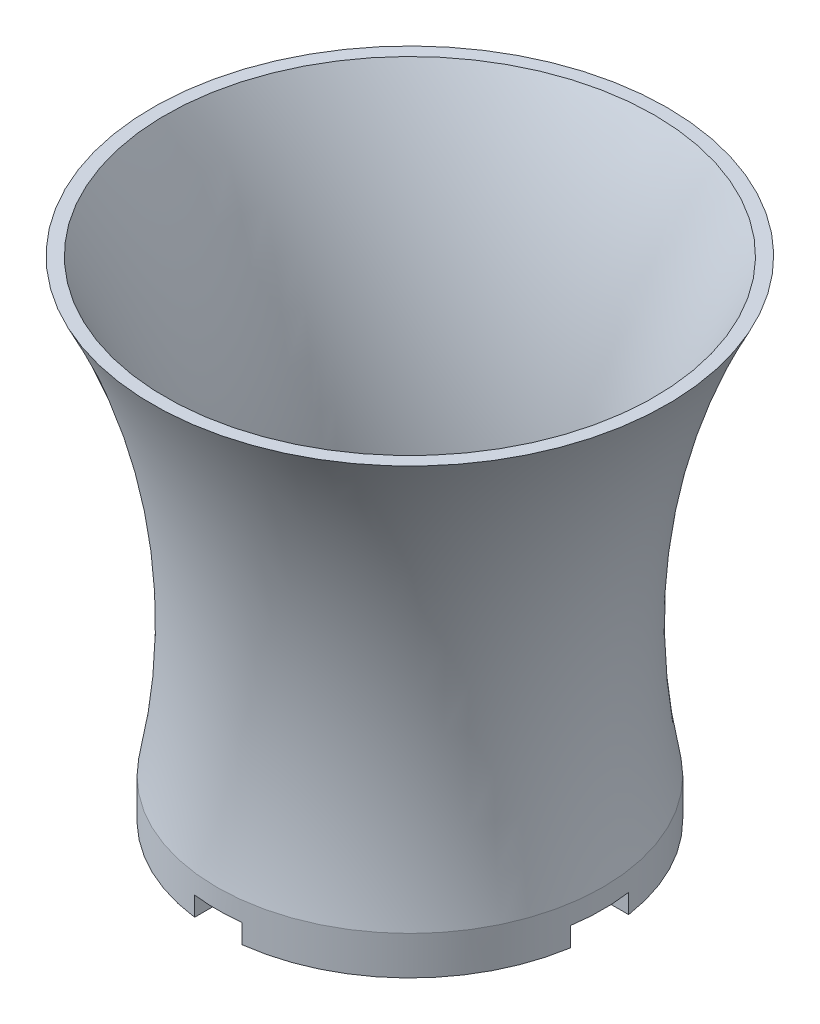
SolidWorks part; units mm, degrees
ref_plane "Front Plane" through (0, 0, 0) normal (0, 0, 1) x (1, 0, 0)
ref_plane "Top Plane" through (0, 0, 0) normal (0, 1, 0) x (1, 0, 0)
ref_plane "Right Plane" through (0, 0, 0) normal (1, 0, 0) x (0, 0, -1)
sketch "Sketch2" plane through (0, 0, 0) normal (0, 0, 1) x (1, 0, 0)
  line L0 (0, 0) -> (-35.56, 0)
  line L2 (-48.26, 88.9) -> (-50.8, 88.9)
  line L3 (-50.8, 88.9) -> (-48.26, 88.9) construction
  line L4 (0, 0) -> (0, 88.9) construction
  line L5 (-35.5254, 26.3207) -> (-32.9854, 26.3207) construction
  line L6 (-38.1, 0) -> (-38.1, -7.62)
  line L7 (-38.1, -7.62) -> (0, -7.62)
  line L8 (0, -7.62) -> (0, 0)
  arc A0 (-50.8, 88.9) -> (-38.1, 0) centre (-171.3551, 26.3207) cw
  arc A1 (-48.26, 88.9) -> (-35.56, 0) centre (-170.4492, 26.0873) cw
revolve "Revolve1" add sketch "Sketch2" angle 360 about L4
hole_wizard "9/64 (0.14063) Diameter Hole2" positions "Sketch8" profile "Sketch7" hole size "9/64" standard "ANSI Inch" end condition up to next
sketch "Sketch8" plane through (0, 0, 0) normal (0, 1, 0) x (1, 0, 0)
  point P0 (0, -28.7264)
  point P2 (-28.3897, 0)
  point P4 (0, 28.7264)
  point P6 (28.1202, 0)
  point P8 (17.8151, -20.1051)
  point P10 (17.8151, 19.4316)
  point P12 (-18.4213, 19.4316)
  point P14 (-18.4213, -20.1051)
  point P16 (0, 0)
sketch "Sketch7" plane through (0, 0, 28.7264) normal (1, 0, 0) x (0, 0, 1)
  line L0 (0, 0) -> (0, 7.62)
  line L1 (0, 7.62) -> (1.786, 7.62)
  line L2 (1.786, 7.62) -> (1.786, 0.5328)
  line L3 (1.786, 0.5328) -> (2.421, 0)
  line L5 (2.421, 0) -> (0, 0)
  line L6 (-1.786, 0.5328) -> (-2.421, 0) construction
  line L11 (0, -6.35) -> (0, 107.95) construction
  dimension "Thru Hole Dia." = 3.572
  dimension "Thru Hole Depth" = 7.62
  dimension "Near C'Sink Dia." = 4.842
  dimension "Near C'Sink Angle" = 100
hole_wizard "9/64 (0.14063) Diameter Hole3" positions "Sketch9" profile "Sketch10" hole size "9/64" standard "ANSI Inch" end condition up to next
sketch "Sketch9" plane through (0, -7.62, 0) normal (0, -1, 0) x (-1, 0, 0)
  point P0 (-6.3649, 18.9601)
  point P2 (7.51, 18.9601)
  point P4 (19.8357, 7.9141)
  point P6 (-19.2969, 7.9141)
  point P8 (-19.2969, -8.3856)
  point P10 (-7.0385, -21.3175)
  point P12 (7.9141, -21.3175)
  point P14 (19.8357, -8.857)
sketch "Sketch10" plane through (6.3649, -7.62, -18.9601) normal (1, 0, 0) x (0, 0, -1)
  line L0 (0, 0) -> (0, 7.62)
  line L1 (0, 7.62) -> (1.786, 7.62)
  line L2 (1.786, 7.62) -> (1.786, 0.5328)
  line L3 (1.786, 0.5328) -> (2.421, 0)
  line L5 (2.421, 0) -> (0, 0)
  line L6 (-1.786, 0.5328) -> (-2.421, 0) construction
  line L11 (0, -6.35) -> (0, 107.95) construction
  dimension "Thru Hole Dia." = 3.572
  dimension "Thru Hole Depth" = 7.62
  dimension "Near C'Sink Dia." = 4.842
  dimension "Near C'Sink Angle" = 100
sketch "Sketch11" plane through (0, -7.62, 0) normal (0, -1, 0) x (1, 0, 0)
  line L0 (-4.6966, 37.8094) -> (-4.6966, 30.7269)
  line L2 (4.6966, -37.8094) -> (4.6966, -30.7269)
  line L3 (-4.6966, -30.7269) -> (-4.6966, -37.8094)
  line L4 (37.6302, 5.9646) -> (30.5062, 5.9646)
  line L5 (37.7019, -5.4931) -> (30.5946, -5.4931)
  line L6 (4.6966, 30.7269) -> (4.6966, 37.8094)
  line L7 (-30.5062, 5.9646) -> (-37.6302, 5.9646)
  line L8 (-30.5946, -5.4931) -> (-37.7019, -5.4931)
  circle A0 centre (0, 0) radius 38.1 construction
  circle A1 centre (0, 0) radius 38.1 construction
  arc A5 (-37.6302, 5.9646) -> (-37.7019, -5.4931) centre (0, 0) ccw
  arc A6 (-4.6966, 30.7269) -> (-30.5062, 5.9646) centre (0, 0) ccw
  arc A7 (-30.5946, -5.4931) -> (-4.6966, -30.7269) centre (0, 0) ccw
  arc A8 (30.5062, 5.9646) -> (4.6966, 30.7269) centre (0, 0) ccw
  arc A9 (4.6966, -30.7269) -> (30.5946, -5.4931) centre (0, 0) ccw
  arc A10 (4.6966, 37.8094) -> (-4.6966, 37.8094) centre (0, 0) ccw
  arc A11 (37.7019, -5.4931) -> (37.6302, 5.9646) centre (0, 0) ccw
  arc A12 (-4.6966, -37.8094) -> (4.6966, -37.8094) centre (0, 0) ccw
extrude "Cut-Extrude1" cut sketch "Sketch11" against normal blind 3.81
